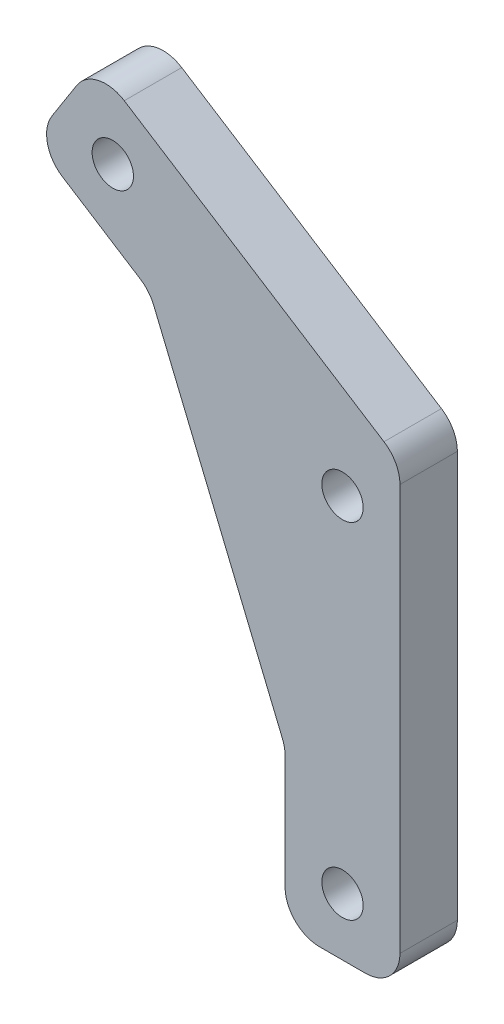
SolidWorks part; units mm, degrees
ref_plane "Front Plane" through (0, 0, 0) normal (0, 0, 1) x (1, 0, 0)
ref_plane "Top Plane" through (0, 0, 0) normal (0, 1, 0) x (1, 0, 0)
ref_plane "Right Plane" through (0, 0, 0) normal (1, 0, 0) x (0, 0, -1)
sketch "Sketch1" plane through (0, 0, 0) normal (0, 0, 1) x (1, 0, 0)
  line L0 (-34.1675, 55.2068) -> (-6.35, 37.483)
  line L1 (-6.35, 37.483) -> (-6.35, -6.35)
  line L2 (-6.35, -6.35) -> (6.35, -6.35)
  line L3 (6.35, -6.35) -> (6.35, 44.45)
  line L4 (6.35, 44.45) -> (-27.3432, 65.9175)
  line L5 (-27.3432, 65.9175) -> (-34.1675, 55.2068)
  circle A0 centre (0, 0) radius 2.286
  circle A1 centre (0, 38.1) radius 2.286
  circle A2 centre (-25.4, 57.15) radius 2.286
  point P9 (0, 0)
  point P14 (-18.9975, 28.1289)
  point P15 (4.3033, 12.4901)
  point P16 (-22.2512, 37.0504)
  point P19 (-1.9648, 20.2528)
  dimension "D4" = 4.572
  dimension "D10" = 4.572
  dimension "D1" = 12.7
  dimension "D2" = 6.35
  dimension "D3" = 6.35
  dimension "D5" = 38.1
  dimension "D6" = 6.35
  dimension "D7" = 6.35
  dimension "D8" = 6.35
  dimension "D9" = 12.7
  dimension "D11" = 19.05
  dimension "D12" = 25.4
extrude "Boss-Extrude1" add sketch "Sketch1" along normal blind 6.35
chamfer "Chamfer1" distance 17.78 angle 35 1 edges at (-6.35, 37.483, 3.175)
fillet "Fillet1" radius 3.81 7 edges at (-27.3432, 65.9175, 3.175) (6.35, 44.45, 3.175) (6.35, -6.35, 3.175) (-6.35, -6.35, 3.175) (-6.35, 10.8304, 3.175) (-21.345, 47.037, 3.175) (-34.1675, 55.2068, 3.175)
